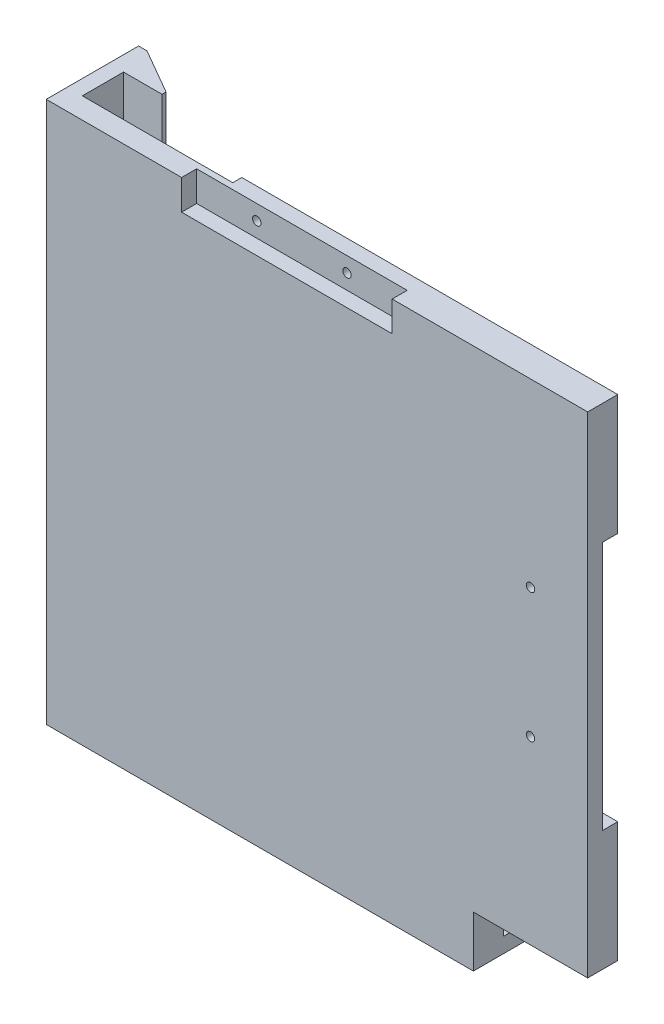
SolidWorks part; units mm, degrees
ref_plane "Alzado" through (0, 0, 0) normal (0, 0, 1) x (1, 0, 0)
ref_plane "Planta" through (0, 0, 0) normal (0, 1, 0) x (1, 0, 0)
ref_plane "Vista lateral" through (0, 0, 0) normal (1, 0, 0) x (0, 0, -1)
sketch "Croquis1" plane through (0, 0, 0) normal (0, 0, 1) x (1, 0, 0)
  line L1 (0, 0) -> (180, 0)
  line L2 (0, 0) -> (0, 180)
  line L3 (0, 180) -> (180, 180)
  line L4 (180, 0) -> (180, 180)
  dimension "D1" = 180
extrude "Saliente-Extruir1" add sketch "Croquis1" along normal blind 30.7
sketch "Croquis2" plane through (0, 0, 0) normal (0, 0, -1) x (-1, 0, 0)
  line L0 (-180, 0) -> (-180, 180) construction
  line L1 (-180, 17.01) -> (-17.79, 17.01)
  line L2 (-180, 17.01) -> (-180, 180)
  line L3 (-180, 180) -> (-17.79, 180)
  line L4 (-17.79, 17.01) -> (-17.79, 180)
  line L5 (-180, 180) -> (0, 180) construction
  line L6 (0, 180) -> (0, 0) construction
  line L7 (0, 0) -> (-180, 0) construction
  dimension "D1" = 17.79
  dimension "D2" = 17.01
extrude "Cortar-Extruir1" cut sketch "Croquis2" against normal blind 20.7
sketch "Croquis4" plane through (0, 180, 0) normal (0, 1, 0) x (1, 0, 0)
  line L0 (17.79, -20.7) -> (17.79, 0) construction
  line L1 (180, -20.7) -> (5, -20.7)
  line L2 (180, -20.7) -> (180, -10)
  line L3 (180, -10) -> (5, -10)
  line L4 (5, -20.7) -> (5, -10)
  dimension "D1" = 10.7
  dimension "D2" = 12.79
extrude "Cortar-Extruir2" cut sketch "Croquis4" against normal offset from surface (175 mm away) 5 up to face at (90, 0, 15.35)
sketch "Croquis5" plane through (0, 0, 0) normal (0, -1, 0) x (1, 0, 0)
  line L0 (0, 0) -> (180, 0) construction
  line L1 (180, 30.7) -> (142, 30.7)
  line L2 (180, 30.7) -> (180, 0)
  line L3 (180, 0) -> (142, 0)
  line L4 (142, 30.7) -> (142, 0)
  dimension "D1" = 38
extrude "Cortar-Extruir3" cut sketch "Croquis5" against normal up to surface (17.01 mm away) up to face at (98.895, 17.01, 5)
sketch "Croquis6" plane through (0, 0, 20.7) normal (0, 0, -1) x (-1, 0, 0)
  line L0 (-180, 180) -> (-180, 17.01) construction
  line L1 (-180, 57.01) -> (-142, 57.01)
  line L2 (-180, 57.01) -> (-180, 140)
  line L3 (-180, 140) -> (-142, 140)
  line L4 (-142, 57.01) -> (-142, 140)
  line L5 (-142, 5) -> (-142, 17.01) construction
  line L6 (-5, 180) -> (-180, 180) construction
  line L7 (-142, 17.01) -> (-180, 17.01) construction
  dimension "D1" = 40
  dimension "D2" = 40
extrude "Cortar-Extruir4" cut sketch "Croquis6" against normal blind 5
sketch "Croquis7" plane through (0, 0, 20.7) normal (0, 0, -1) x (-1, 0, 0)
  line L0 (-5, 180) -> (-180, 180) construction
  line L1 (-5, 5) -> (-55, 5)
  line L2 (-5, 5) -> (-5, 180)
  line L3 (-5, 180) -> (-55, 180)
  line L4 (-55, 5) -> (-55, 180)
  dimension "D1" = 50
extrude "Cortar-Extruir5" cut sketch "Croquis7" against normal blind 3
sketch "Croquis8" plane through (0, 0, 30.7) normal (0, 0, 1) x (1, 0, 0)
  line L0 (180, 180) -> (0, 180) construction
  line L1 (45, 170) -> (115, 170)
  line L2 (45, 170) -> (45, 180)
  line L3 (45, 180) -> (115, 180)
  line L4 (115, 170) -> (115, 180)
extrude "Cortar-Extruir6" cut sketch "Croquis8" against normal blind 5
chamfer "Chaflán1" distance 15 angle 30 2 edges at (79.895, 17.01, 0) (17.79, 98.505, 0)
sketch "Croquis9" plane through (0, 0, 20.7) normal (0, 0, -1) x (-1, 0, 0)
  circle A0 centre (-161, 77.01) radius 1.4
  circle A1 centre (-161, 120) radius 1.4
  circle A2 centre (-65, 175) radius 1.4
  circle A3 centre (-95, 175) radius 1.4
extrude "Cortar-Extruir7" cut sketch "Croquis9" against normal blind 20
